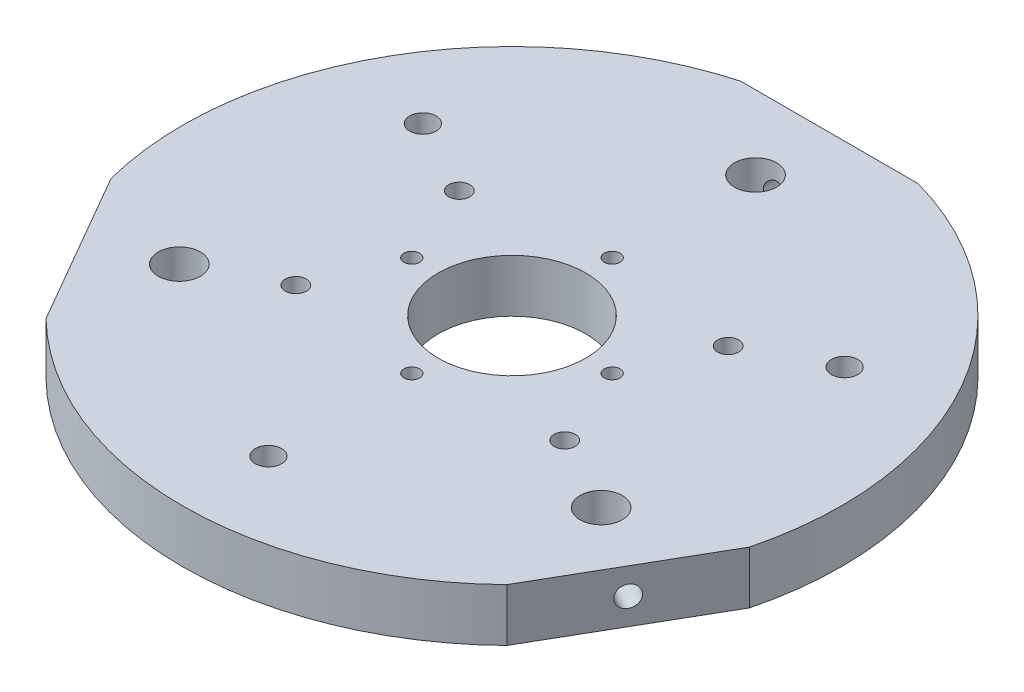
SolidWorks part; units mm, degrees
material "1060 Alloy"
ref_plane "Front Plane" through (0, 0, 0) normal (0, 0, 1) x (1, 0, 0)
ref_plane "Top Plane" through (0, 0, 0) normal (0, 1, 0) x (1, 0, 0)
ref_plane "Right Plane" through (0, 0, 0) normal (1, 0, 0) x (0, 0, -1)
sketch "Sketch1" plane through (0, 0, 0) normal (0, 1, 0) x (1, 0, 0)
  line L0 (-40, -23.094) -> (40, -23.094) construction
  line L1 (40, -23.094) -> (0, 46.188) construction
  line L2 (0, 46.188) -> (-40, -23.094) construction
  line L3 (-40, -23.094) -> (-54.1266, -31.25) construction
  circle A0 centre (0, 46.188) radius 4
  circle A1 centre (40, -23.094) radius 4
  circle A2 centre (-40, -23.094) radius 4
  circle A3 centre (0, 0) radius 62.5
  dimension "D4" = 8
  dimension "D5" = 8
  dimension "D6" = 8
  dimension "D7" = 125
  dimension "D1" = 80
  dimension "D2" = 80
  dimension "D3" = 80
extrude "Boss-Extrude1" add sketch "Sketch1" along normal blind 10
sketch "Sketch2" plane through (0, 10, 0) normal (0, 1, 0) x (1, 0, 0)
  line L0 (0, 0) -> (-40, -23.094) construction
  line L1 (-40, -23.094) -> (-67.1185, -38.7509) construction
  line L2 (0, 0) -> (40, -23.094) construction
  line L3 (40, -23.094) -> (73.8523, -42.6387) construction
  line L4 (0, 0) -> (0, 46.188) construction
  line L5 (0, 46.188) -> (0, 68.5159) construction
  line L6 (-68.6615, -1.4509) -> (-25.024, -77.0333) construction
  line L7 (63.3211, -10.7007) -> (40.6097, -50.0381) construction
  line L8 (-14.2926, 60.188) -> (16.8158, 60.188) construction
  line L9 (-39.5818, -51.8183) -> (-64.7131, -8.2897)
  line L10 (-39.5818, -51.8183) -> (-52.5562, -59.309)
  line L11 (-64.7131, -8.2897) -> (-77.6875, -15.7805)
  line L12 (-52.5562, -59.309) -> (-77.6875, -15.7805)
  line L13 (40.6097, -50.0381) -> (63.3211, -10.7007)
  line L14 (40.6097, -50.0381) -> (52.9299, -57.1511)
  line L15 (63.3211, -10.7007) -> (75.6413, -17.8138)
  line L16 (52.9299, -57.1511) -> (75.6413, -17.8138)
  line L17 (-21.515, 60.188) -> (22.4572, 60.188)
  line L18 (-21.515, 60.188) -> (-21.515, 68.9)
  line L19 (22.4572, 60.188) -> (22.4572, 68.9)
  line L20 (-21.515, 68.9) -> (22.4572, 68.9)
  point P13 (-52.1244, -30.094)
  point P16 (52.1244, -30.094)
  point P19 (0, 60.188)
  dimension "D2" = 14
  dimension "D3" = 14
  dimension "D4" = 14
extrude "Cut-Extrude1" cut sketch "Sketch2" against normal blind 10
sketch "Sketch3" plane through (52.1244, 0, 30.094) normal (0.866, 0, 0.5) x (0.5, 0, -0.866)
  line L0 (16.842, 10) -> (-16.842, 10) construction
  line L1 (-16.842, 0) -> (-16.842, 10) construction
  line L2 (16.842, 10) -> (16.842, 0) construction
  circle A0 centre (0.002, 5) radius 2
  point P9 (16.842, 5)
  dimension "D1" = 4
  dimension "D2" = 5
  dimension "D3" = 33.6839
  dimension "D4" = 16.84
extrude "Cut-Extrude2" cut sketch "Sketch3" against normal blind 12
sketch "Sketch4" plane through (-52.1244, 0, 30.094) normal (-0.866, 0, 0.5) x (0.5, 0, 0.866)
  line L0 (16.842, 10) -> (-16.842, 10) construction
  line L1 (-16.842, 0) -> (-16.842, 10) construction
  line L2 (16.842, 10) -> (16.842, 0) construction
  circle A0 centre (-0.002, 5) radius 2
  dimension "D1" = 4
  dimension "D2" = 5
  dimension "D3" = 16.84
  dimension "D4" = 33.6839
extrude "Cut-Extrude3" cut sketch "Sketch4" against normal blind 12
sketch "Sketch5" plane through (0, 0, -60.188) normal (0, 0, -1) x (-1, 0, 0)
  line L0 (16.842, 10) -> (-16.842, 10) construction
  line L1 (-16.842, 0) -> (-16.842, 10) construction
  line L2 (16.842, 10) -> (16.842, 0) construction
  circle A0 centre (-0.002, 5) radius 2
  dimension "D1" = 4
  dimension "D2" = 5
  dimension "D3" = 33.6839
  dimension "D4" = 16.84
extrude "Cut-Extrude4" cut sketch "Sketch5" against normal blind 12
sketch "Sketch6" plane through (0, 10, 0) normal (0, 1, 0) x (1, 0, 0)
  circle A0 centre (0, 0) radius 14
  dimension "D1" = 28
extrude "Cut-Extrude5" cut sketch "Sketch6" against normal blind 12
sketch "Sketch7" plane through (0, 10, 0) normal (0, 1, 0) x (1, 0, 0)
  circle A1 centre (0, 19) radius 1.5
  circle A2 centre (19, 0) radius 1.5
  circle A3 centre (0, -19) radius 1.5
  circle A4 centre (-19, 0) radius 1.5
  point P13 (0, 0)
  point P17 (0, 0)
  dimension "D2" = 3
  dimension "D3" = 4
extrude "Cut-Extrude6" cut sketch "Sketch7" against normal blind 10
sketch "Sketch8" plane through (0, 10, 0) normal (0, 1, 0) x (1, 0, 0)
  circle A0 centre (-25.5, 15.5) radius 2
  circle A1 centre (25.5, 15.5) radius 2
  circle A2 centre (25.5, -15.5) radius 2
  circle A3 centre (-25.5, -15.5) radius 2
  point P0 (0, 0)
  dimension "D3" = 4
  dimension "D1" = 31
  dimension "D2" = 51
extrude "Cut-Extrude7" cut sketch "Sketch8" against normal blind 10
sketch "Sketch9" plane through (0, 10, 0) normal (0, 1, 0) x (1, 0, 0)
  line L0 (0, 0) -> (-40, 23.094) construction
  line L1 (0, 0) -> (40, 23.094) construction
  line L2 (0, 0) -> (0, -46.188) construction
  line L3 (0, 46.188) -> (0, 0) construction
  circle A1 centre (-40, 23.094) radius 2.5
  circle A2 centre (40, 23.094) radius 2.5
  circle A3 centre (0, -46.188) radius 2.5
  dimension "D4" = 5
  dimension "D5" = 5
  dimension "D6" = 5
  dimension "D1" = 60
  dimension "D2" = 60
  dimension "D3" = 120
extrude "Cut-Extrude8" cut sketch "Sketch9" against normal blind 10
